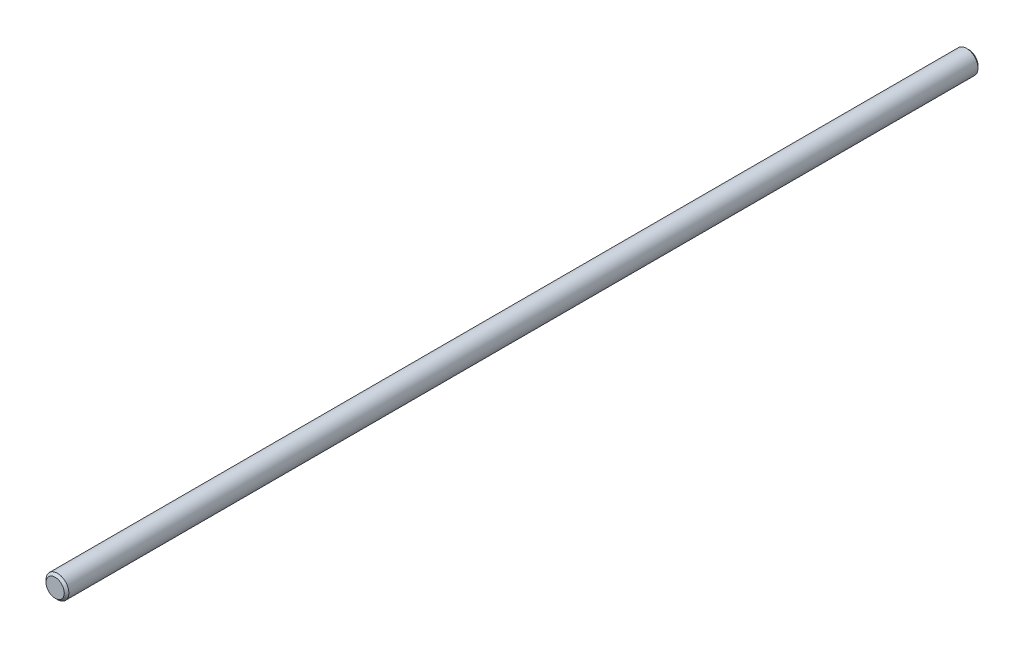
SolidWorks part; units mm, degrees
ref_plane "Front" through (0, 0, 0) normal (0, 0, 1) x (1, 0, 0)
ref_plane "Top" through (0, 0, 0) normal (0, 1, 0) x (1, 0, 0)
ref_plane "Right" through (0, 0, 0) normal (1, 0, 0) x (0, 0, -1)
sketch "Sketch1" plane through (0, 0, 0) normal (0, 0, 1) x (1, 0, 0)
  circle A0 centre (0, 0) radius 1.5875 construction
  dimension "Diameter" = 3.175
sketch "Sketch2" plane through (0, 0, 0) normal (1, 0, 0) x (0, 0, -1)
  line L0 (-63.5, 0) -> (63.5, 0) construction
  line L1 (5.2388, 0) -> (-5.2388, 0) construction
  line L3 (63.5, 1.5875) -> (63.5, -1.5875) construction
  line L4 (-63.5, 1.5875) -> (-63.5, -1.5875) construction
  line L5 (-59.5312, 1.5875) -> (-59.5312, -1.5875) construction
  line L6 (59.5312, 1.5875) -> (59.5312, -1.5875) construction
  point P6 (0, 0)
  point P10 (63.5, 0)
  point P13 (-63.5, 0)
  point P16 (-59.5312, 0)
  point P19 (59.5312, 0)
  dimension "D1" = 3.175
  dimension "Length" = 127
  dimension "D2" = 3.9688
  dimension "D3" = 3.9688
sketch "Sketch3" plane through (0, 0, 0) normal (0, 0, 1) x (1, 0, 0)
  line L0 (0, 1.5875) -> (0, -1.5875) construction
  circle A0 centre (0, 0) radius 1.5875
  dimension "D1" = 3.175
extrude "Boss-Extrude1" add sketch "Sketch3" along normal mid plane 127
chamfer "Chamfer1" distance 0.3175 angle 45 2 edges at (1.5875, 0, -63.5) (1.5875, 0, 63.5)
equation "\"D1@Sketch2\" = \"Diameter@Sketch1\""
equation "\"D1@Sketch3\" = \"Diameter@Sketch1\""
equation "\"D1@Boss-Extrude1\" = \"Length@Sketch2\""
equation "\"D1@Chamfer1\" = \"Diameter@Sketch1\" * .1"
equation "\"D2@Sketch2\"=\"Diameter@Sketch1\"*1.25"
equation "\"D3@Sketch2\"=\"D2@Sketch2\""
